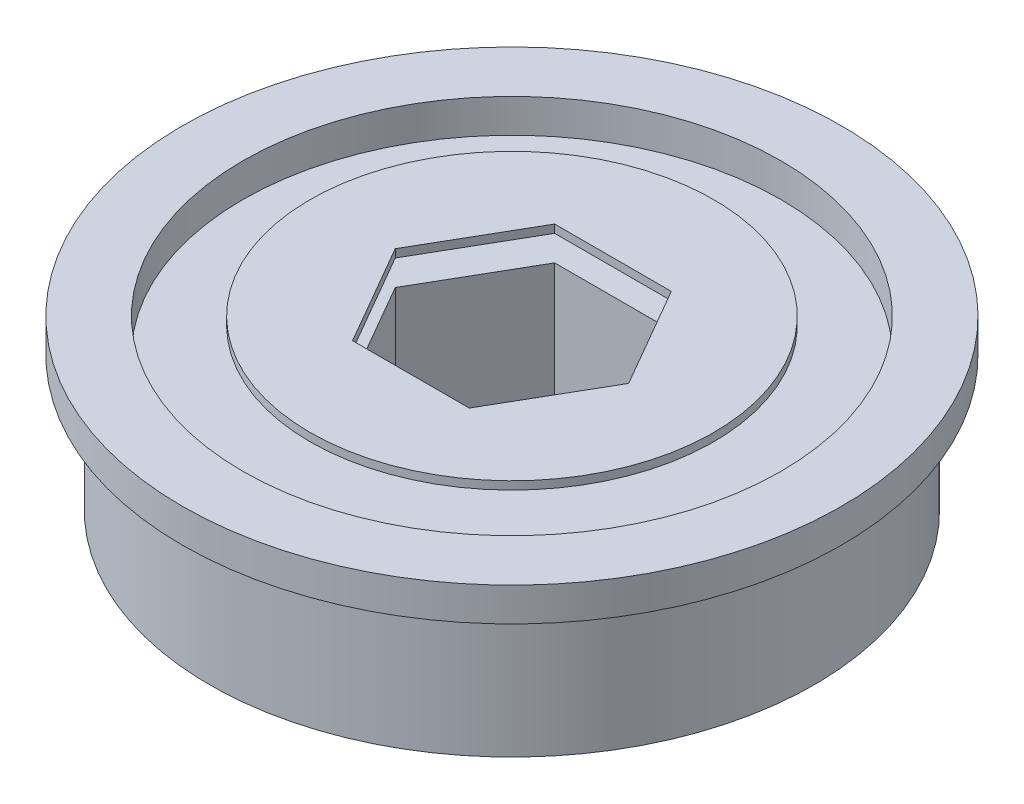
SolidWorks part; units mm, degrees
ref_plane "Front Plane" through (0, 0, 0) normal (0, 0, 1) x (1, 0, 0)
ref_plane "Top Plane" through (0, 0, 0) normal (0, 1, 0) x (1, 0, 0)
ref_plane "Right Plane" through (0, 0, 0) normal (1, 0, 0) x (0, 0, -1)
ref_plane "Plane1" through (0, 0, 0) normal (0, 0, -1) x (-1, 0, 0)
sketch "Sketch1" plane through (0, 0, 0) normal (0, 0, -1) x (-1, 0, 0)
  line L0 (-15.5575, 6.35) -> (0, 6.35)
  line L1 (0, 6.35) -> (0, 7.9375)
  line L2 (0, 7.9375) -> (-15.5575, 7.9375)
  line L3 (-15.5575, 7.9375) -> (-15.5575, 6.35)
  line L4 (0, 6.35) -> (0, 7.9375) construction
revolve "Revolve1" add sketch "Sketch1" angle 360 about L4
hole_wizard "M22 Clearance Hole1" positions "Sketch3" profile "Sketch2" hole size "M22" standard "ANSI Metric"
sketch "Sketch3" plane through (0, 7.9375, 0) normal (0, 1, 0) x (1, 0, 0)
  point P0 (0, 0)
sketch "Sketch2" plane through (0, 7.9375, 0) normal (1, 0, 0) x (0, 0, 1)
  line L0 (0, 0) -> (0, 1.5875)
  line L1 (0, 1.5875) -> (12.7, 1.5875)
  line L2 (12.7, 1.5875) -> (12.7, 0)
  line L5 (12.7, 0) -> (0, 0)
  line L11 (0, -6.35) -> (0, 107.95) construction
  dimension "Thru Hole Dia." = 25.4
  dimension "Thru Hole Depth" = 1.5875
ref_plane "Plane2" through (0, 7.5565, 0) normal (0, -1, 0) x (1, 0, 0)
sketch "Sketch4" plane through (0, 7.5565, 0) normal (0, -1, 0) x (1, 0, 0)
  circle A0 centre (0, 0) radius 9.525
extrude "Boss-Extrude1" add sketch "Sketch4" against normal blind 0.381
sketch "Sketch5" plane through (0, 6.35, 0) normal (0, -1, 0) x (1, 0, 0)
  circle A0 centre (0, 0) radius 14.2748
extrude "Boss-Extrude2" add sketch "Sketch5" along normal blind 6.35
sketch "Sketch6" plane through (0, 0, 0) normal (0, -1, 0) x (1, 0, 0)
  line L0 (-5.5079, 0) -> (-2.754, -4.77)
  line L1 (-2.754, -4.77) -> (2.754, -4.77)
  line L2 (2.754, -4.77) -> (5.5079, 0)
  line L3 (5.5079, 0) -> (2.754, 4.77)
  line L4 (2.754, 4.77) -> (-2.754, 4.77)
  line L5 (-2.754, 4.77) -> (-5.5079, 0)
extrude "Cut-Extrude1" cut sketch "Sketch6" against normal through all
